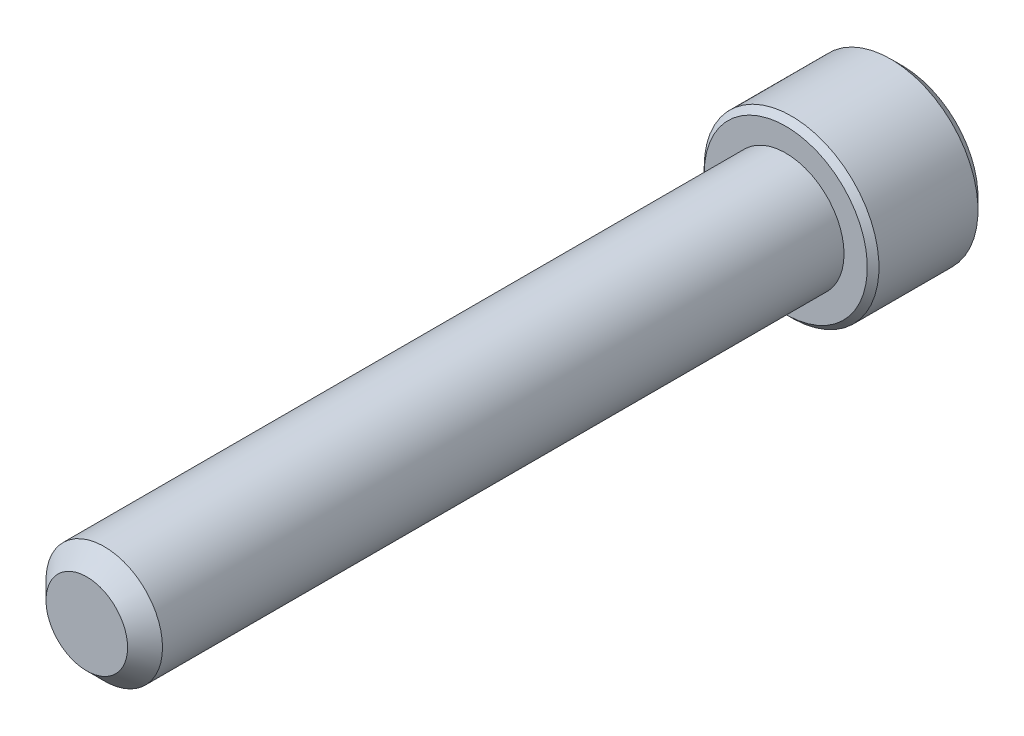
SolidWorks part; units mm, degrees
ref_plane "Front Plane" through (0, 0, 0) normal (0, 0, 1) x (1, 0, 0)
ref_plane "Top Plane" through (0, 0, 0) normal (0, 1, 0) x (1, 0, 0)
ref_plane "Right Plane" through (0, 0, 0) normal (1, 0, 0) x (0, 0, -1)
sketch "Sketch1" plane through (0, 0, 0) normal (0, 0, 1) x (1, 0, 0)
  line L0 (0, 3.175) -> (0, -3.175) construction
  circle A0 centre (0, 0) radius 3.175
  dimension "OD" = 6.35
extrude "Extrude1" add sketch "Sketch1" against normal blind 38.1
sketch "Sketch6" plane through (0, 0, -38.1) normal (0, 0, -1) x (-1, 0, 0)
  circle A0 centre (0, 0) radius 4.7625
  dimension "head dia" = 9.525
extrude "Extrude2" add sketch "Sketch6" along normal blind 6.35
sketch "Sketch7" plane through (0, 0, -44.45) normal (0, 0, -1) x (-1, 0, 0)
  line L1 (0, 2.7496) -> (-2.3812, 1.3748)
  line L2 (-2.3812, 1.3748) -> (-2.3812, -1.3748)
  line L3 (-2.3812, -1.3748) -> (0, -2.7496)
  line L4 (0, -2.7496) -> (2.3812, -1.3748)
  line L5 (2.3812, -1.3748) -> (2.3812, 1.3748)
  line L6 (2.3812, 1.3748) -> (0, 2.7496)
  circle A0 centre (0, 0) radius 2.3813 construction
  dimension "hex dia" = 4.7625
extrude "Cut-Extrude1" cut sketch "Sketch7" against normal blind 3.5719
sketch "Sketch8" plane through (0, 0, -44.45) normal (0, 0, -1) x (-1, 0, 0)
  circle A0 centre (0, 0) radius 2.7496
extrude "Cut-Extrude2" cut sketch "Sketch8" against normal blind 0.635 draft 45
chamfer "Chamfer1" distance 0.635 angle 45 1 edges at (-4.7625, 0, -44.45)
chamfer "Chamfer2" distance 0.3175 angle 45 1 edges at (-4.7625, 0, -38.1)
chamfer "Chamfer3" distance 0.9525 angle 45 1 edges at (3.175, 0, 0)
